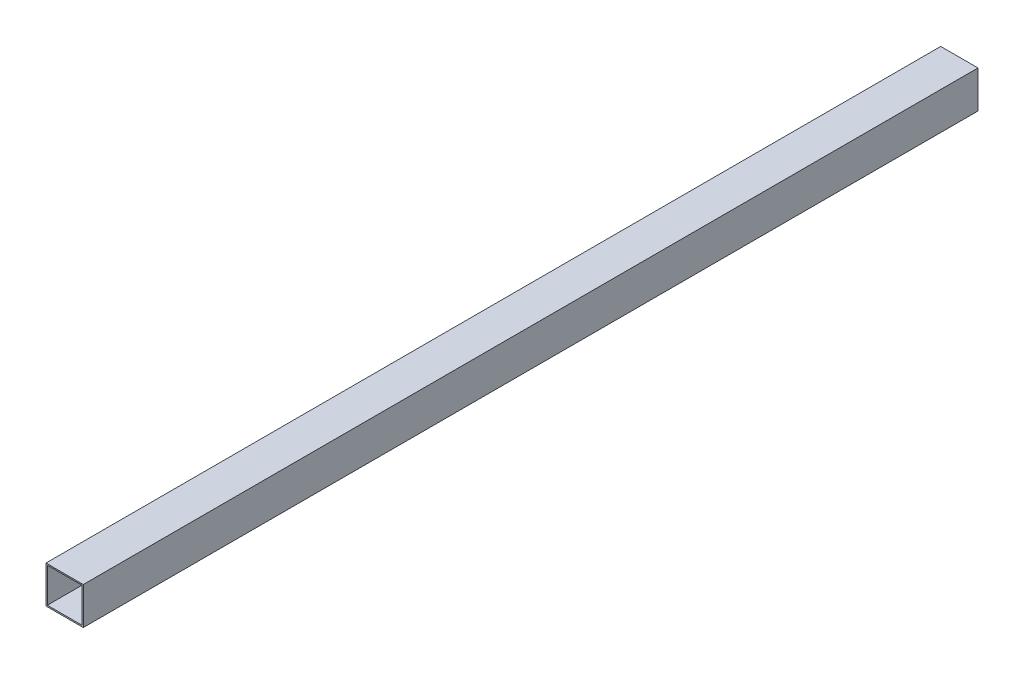
SolidWorks part; units mm, degrees
ref_plane "Front" through (0, 0, 0) normal (0, 0, 1) x (1, 0, 0)
ref_plane "Top" through (0, 0, 0) normal (0, 1, 0) x (1, 0, 0)
ref_plane "Right" through (0, 0, 0) normal (1, 0, 0) x (0, 0, -1)
sketch "草图1" plane through (0, 0, 0) normal (0, 0, 1) x (1, 0, 0)
  line L1 (-16.7875, 20.0303) -> (8.6125, 20.0303)
  line L2 (-16.7875, 20.0303) -> (-16.7875, -5.3697)
  line L3 (-16.7875, -5.3697) -> (8.6125, -5.3697)
  line L4 (8.6125, 20.0303) -> (8.6125, -5.3697)
extrude "凸台-拉伸1" add sketch "草图1" along normal blind 609.6
sketch "草图2" plane through (0, 0, 609.6) normal (0, 0, 1) x (1, 0, 0)
  line L1 (-15.8746, 19.1607) -> (7.6561, 19.1607)
  line L2 (-15.8746, 19.1607) -> (-15.8746, -4.4288)
  line L3 (-15.8746, -4.4288) -> (7.6561, -4.4288)
  line L4 (7.6561, 19.1607) -> (7.6561, -4.4288)
extrude "切除-拉伸1" cut sketch "草图2" against normal blind 609.6
